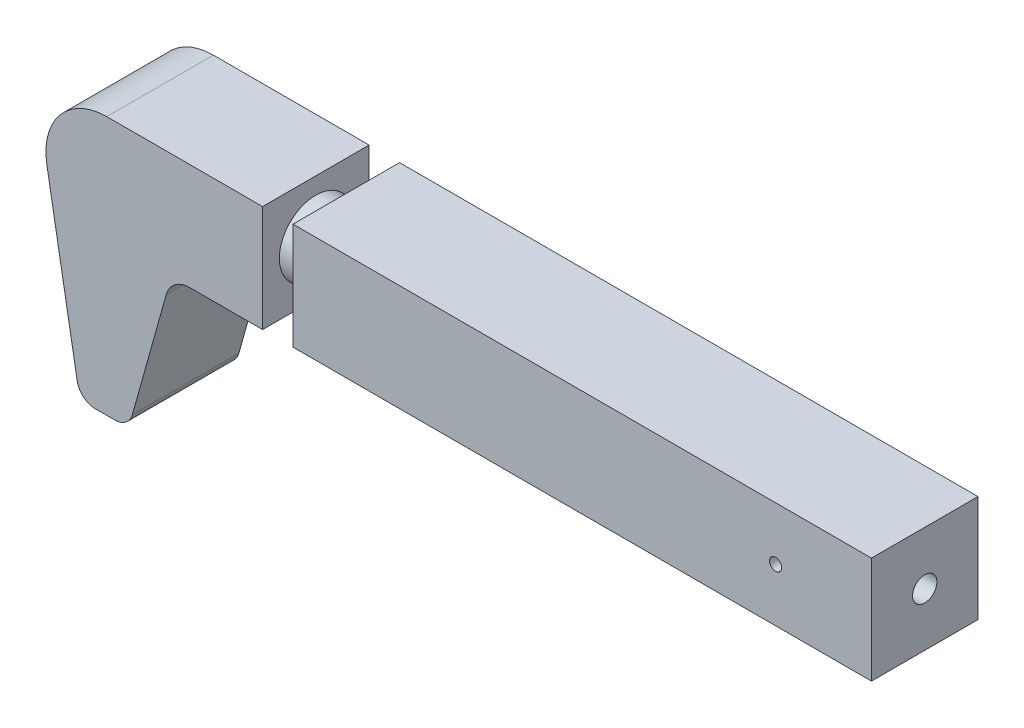
SolidWorks part; units mm, degrees
ref_plane "Front Plane" through (0, 0, 0) normal (0, 0, 1) x (1, 0, 0)
ref_plane "Top Plane" through (0, 0, 0) normal (0, 1, 0) x (1, 0, 0)
ref_plane "Right Plane" through (0, 0, 0) normal (1, 0, 0) x (0, 0, -1)
sketch "Sketch1" plane through (0, 0, 0) normal (0, 0, 1) x (1, 0, 0)
  line L8 (0, 17.5) -> (-25.5825, 17.5)
  line L9 (0, 17.5) -> (0, 0)
  line L10 (0, 0) -> (-11.9669, 0)
  line L11 (-15.8185, -2.9206) -> (-21.3922, -22.8095)
  line L12 (-24.2809, -25) -> (-27.4888, -25)
  line L13 (-30.4432, -22.5209) -> (-35.4305, 5.7635)
  arc A4 (-15.8185, -2.9206) -> (-11.9669, 0) centre (-11.9669, -4) cw
  arc A5 (-35.4305, 5.7635) -> (-25.5825, 17.5) centre (-25.5825, 7.5) cw
  arc A6 (-30.4432, -22.5209) -> (-27.4888, -25) centre (-27.4888, -22) ccw
  arc A7 (-24.2809, -25) -> (-21.3922, -22.8095) centre (-24.2809, -22) ccw
  point P1 (0, 0)
  point P4 (-2.0632, 0)
  point P12 (-15, 0)
  point P15 (-37.5, 17.5)
  point P19 (-30.0061, -25)
  point P22 (-22.0061, -25)
  dimension "D1" = 37.5
  dimension "D2" = 17.5
  dimension "D3" = 15
  dimension "D9" = 4
  dimension "D10" = 10
  dimension "D11" = 3
  dimension "D4" = 25
  dimension "D5" = 8
  dimension "D6" = 260
  dimension "D7" = 0
  dimension "D8" = 0
sketch "Sketch2" plane through (0, 0, 0) normal (1, 0, 0) x (0, 0, -1)
  line L7 (-17.5, 17.5) -> (0, 17.5)
  line L8 (-17.5, 17.5) -> (-17.5, 0)
  line L9 (-17.5, 0) -> (0, 0)
  line L10 (0, 17.5) -> (0, 0)
  point P5 (0, 0)
  point P6 (0, 0)
  point P7 (0, 0)
  point P8 (0, 0)
  point P9 (0, 0)
  dimension "D1" = 17.5
extrude "Boss-Extrude4" add sketch "Sketch2" along normal blind 95 from offset 5
sketch "Sketch3" plane through (100, 0, 0) normal (1, 0, 0) x (0, 0, -1)
  line L2 (0, 17.5) -> (-17.5, 17.5) construction
  line L4 (-17.5, 17.5) -> (-17.5, 0) construction
  circle A0 centre (-8.75, 8.75) radius 2
  dimension "D1" = 4
  dimension "D2" = 8.75
  dimension "D3" = 8.75
sketch "Sketch4" plane through (0, 0, 0) normal (0, 0, -1) x (-1, 0, 0)
  line L2 (-100, 0) -> (-100, 17.5) construction
  line L4 (-100, 17.5) -> (-5, 17.5) construction
  circle A0 centre (-84.25, 8.75) radius 1
  dimension "D2" = 2
  dimension "D1" = 15.75
  dimension "D3" = 8.75
extrude "Cut-Extrude1" cut sketch "Sketch3" against normal blind 50
extrude "Cut-Extrude2" cut sketch "Sketch4" against normal blind 50
sketch "Sketch6" plane through (5, 0, 0) normal (-1, 0, 0) x (0, 0, 1)
  line L0 (17.5, 17.5) -> (17.5, 0) construction
  line L1 (0, 17.5) -> (17.5, 17.5) construction
  circle A0 centre (8.75, 8.75) radius 6
  point P6 (0, 0)
  dimension "D1" = 12
  dimension "D2" = 8.75
  dimension "D3" = 8.75
extrude "Boss-Extrude6" add sketch "Sketch6" along normal blind 5
extrude "Boss-Extrude8" add sketch "Sketch1" along normal blind 17.5
